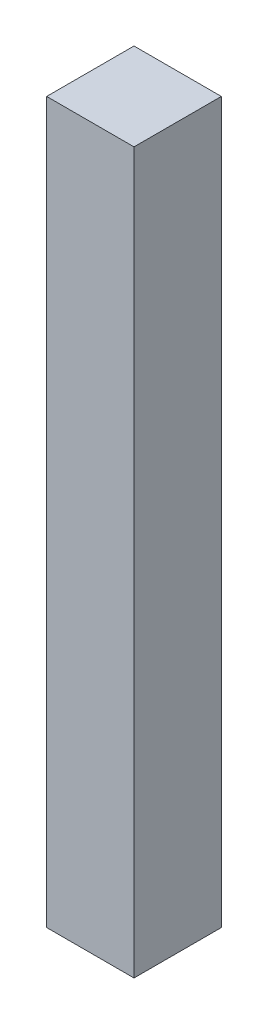
SolidWorks part; units mm, degrees
ref_plane "Front Plane" through (0, 0, 0) normal (0, 0, 1) x (1, 0, 0)
ref_plane "Top Plane" through (0, 0, 0) normal (0, 1, 0) x (1, 0, 0)
ref_plane "Right Plane" through (0, 0, 0) normal (1, 0, 0) x (0, 0, -1)
sketch "Sketch1" plane through (0, 0, 0) normal (0, 1, 0) x (1, 0, 0)
  line L1 (0, 0) -> (20, 0)
  line L2 (0, 0) -> (0, -20)
  line L3 (0, -20) -> (20, -20)
  line L4 (20, 0) -> (20, -20)
extrude "Boss-Extrude1" add sketch "Sketch1" along normal up to surface (164.8292 mm away)
